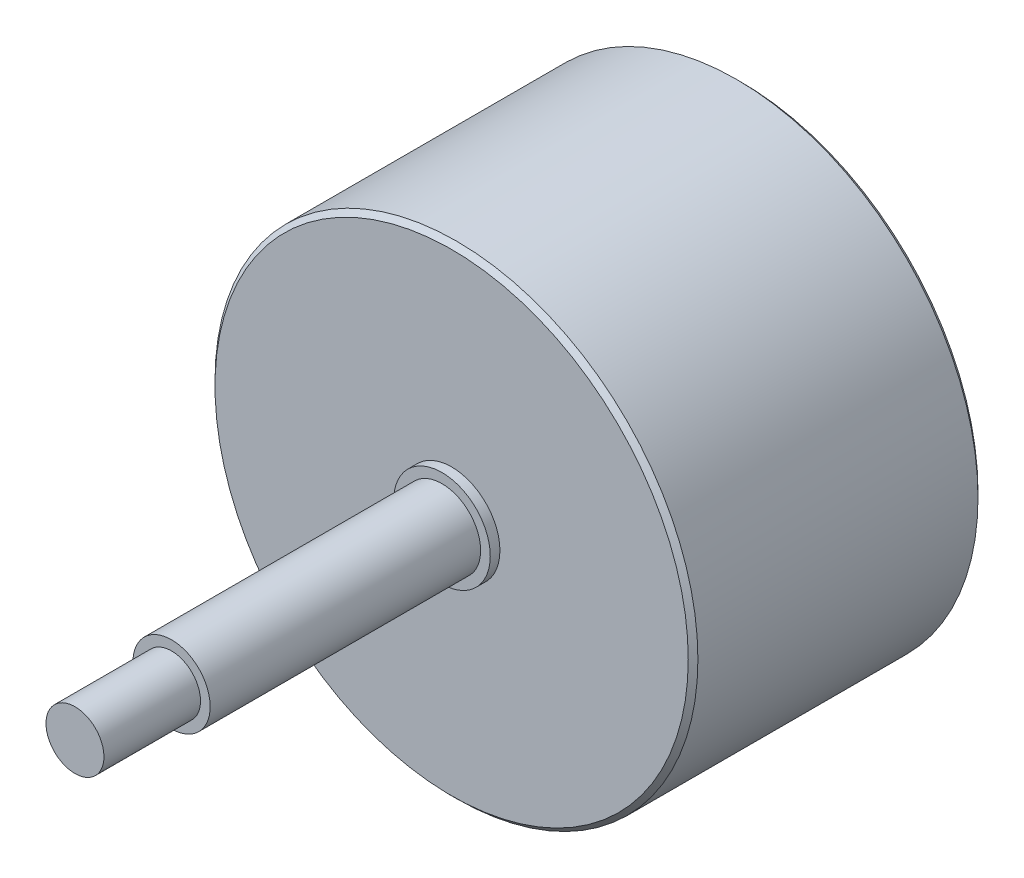
SolidWorks part; units mm, degrees
ref_plane "Plan de face" through (0, 0, 0) normal (0, 0, 1) x (1, 0, 0)
ref_plane "Plan de dessus" through (0, 0, 0) normal (0, 1, 0) x (1, 0, 0)
ref_plane "Plan de droite" through (0, 0, 0) normal (1, 0, 0) x (0, 0, -1)
sketch "Esquisse1" plane through (0, 0, 0) normal (0, 0, 1) x (1, 0, 0)
  circle A0 centre (0, 0) radius 25
  dimension "D1" = 50
extrude "Boss.-Extru.1" add sketch "Esquisse1" along normal blind 30
sketch "Esquisse2" plane through (0, 0, 30) normal (0, 0, 1) x (1, 0, 0)
  circle A0 centre (0, 0) radius 4
  dimension "D1" = 8
extrude "Boss.-Extru.2" add sketch "Esquisse2" along normal blind 39
sketch "Esquisse3" plane through (0, 0, 30) normal (0, 0, 1) x (1, 0, 0)
  circle A0 centre (0, 0) radius 5
  dimension "D1" = 10
extrude "Boss.-Extru.3" add sketch "Esquisse3" along normal blind 1
sketch "Esquisse4" plane through (0, 0, 0) normal (0, 0, -1) x (-1, 0, 0)
  circle A0 centre (0, 0) radius 3
  dimension "D1" = 6
extrude "Enlèv. mat.-Extru.1" cut sketch "Esquisse4" against normal blind 10
chamfer "Chanfrein1" distance 0.5 angle 45 3 edges at (25, 0, 0) (25, 0, 30) (4, 0, 69)
sketch "Esquisse5" plane through (0, 0, 0) normal (1, 0, 0) x (0, 0, -1)
  line L0 (-31, 4) -> (-68.5, 4) construction
  line L1 (-59, 4) -> (-69, 4)
  line L2 (-59, 4) -> (-59, 3)
  line L3 (-59, 3) -> (-69, 3)
  line L4 (-69, 4) -> (-69, 3)
  line L5 (-69, 3.5) -> (-69, -3.5) construction
  line L6 (-69, 0) -> (-52.2606, 0) construction
  dimension "D1" = 1
  dimension "D2" = 10
revolve "Enlèvement de matière-Révolution1" cut sketch "Esquisse5" angle 360 about L6
